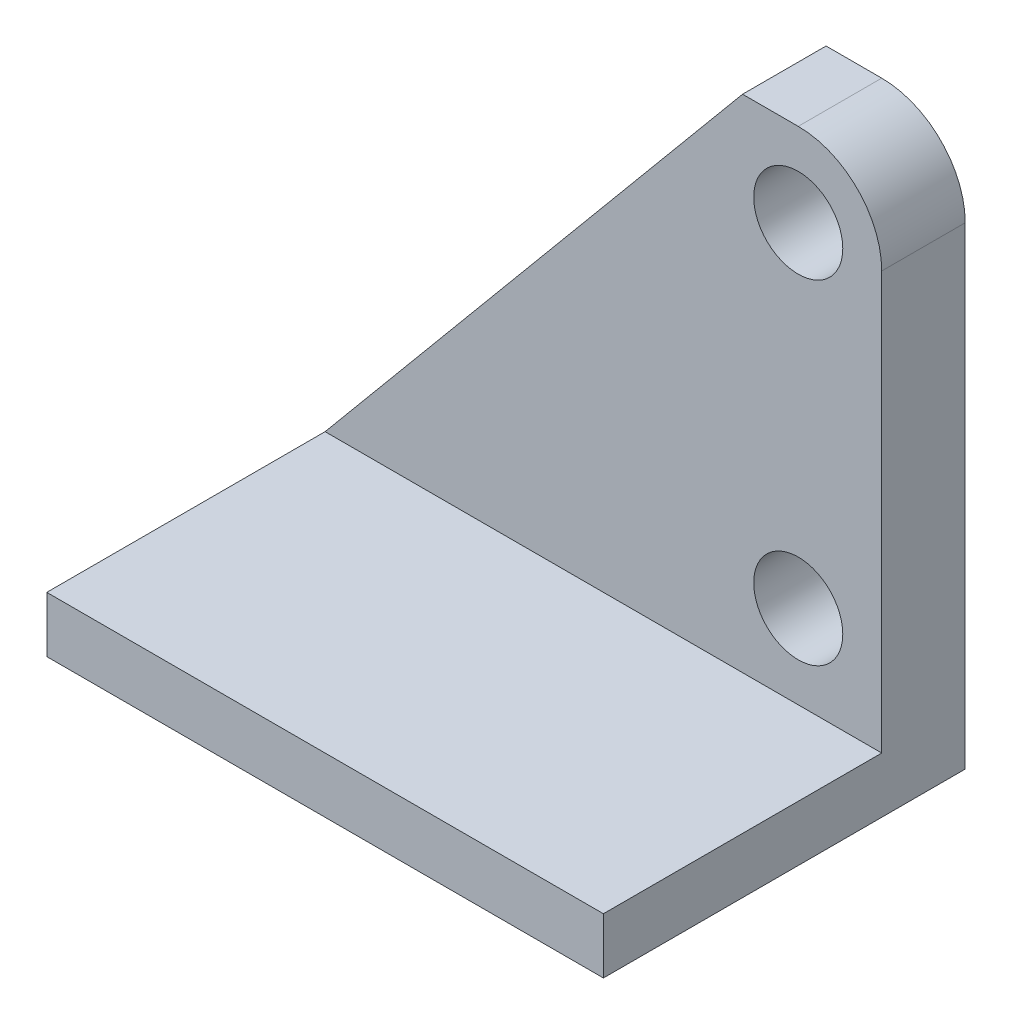
SolidWorks part; units mm, degrees
ref_plane "前视基准面" through (0, 0, 0) normal (0, 0, 1) x (1, 0, 0)
ref_plane "上视基准面" through (0, 0, 0) normal (0, 1, 0) x (1, 0, 0)
ref_plane "右视基准面" through (0, 0, 0) normal (1, 0, 0) x (0, 0, -1)
sketch "草图1" plane through (0, 0, 0) normal (0, 0, 1) x (1, 0, 0)
  line L1 (0, 0) -> (20, 0)
  line L2 (0, 0) -> (0, 20)
  line L3 (0, 20) -> (17, 20)
  line L4 (20, 0) -> (20, 17)
  circle A0 centre (17, 17) radius 1.6
  circle A2 centre (17, 5) radius 1.6
  arc A3 (20, 17) -> (17, 20) centre (17, 17) ccw
  dimension "D1" = 2
  dimension "D2" = 3
extrude "凸台-拉伸1" add sketch "草图1" along normal blind 3
sketch "草图2" plane through (0, 0, 3) normal (0, 0, 1) x (1, 0, 0)
  line L0 (0, 20) -> (0, 0) construction
  line L1 (20, 0) -> (0, 0)
  line L2 (20, 0) -> (20, 2)
  line L3 (20, 2) -> (0, 2)
  line L4 (0, 0) -> (0, 2)
extrude "凸台-拉伸2" add sketch "草图2" along normal blind 10
sketch "草图3" plane through (0, 0, 3) normal (0, 0, 1) x (1, 0, 0)
  line L0 (0, 2) -> (15, 20)
  line L1 (17, 20) -> (0, 20) construction
  line L2 (15, 20) -> (0, 20)
  line L3 (0, 20) -> (0, 2)
  point P5 (0, 0)
extrude "切除-拉伸1" cut sketch "草图3" against normal blind 20
